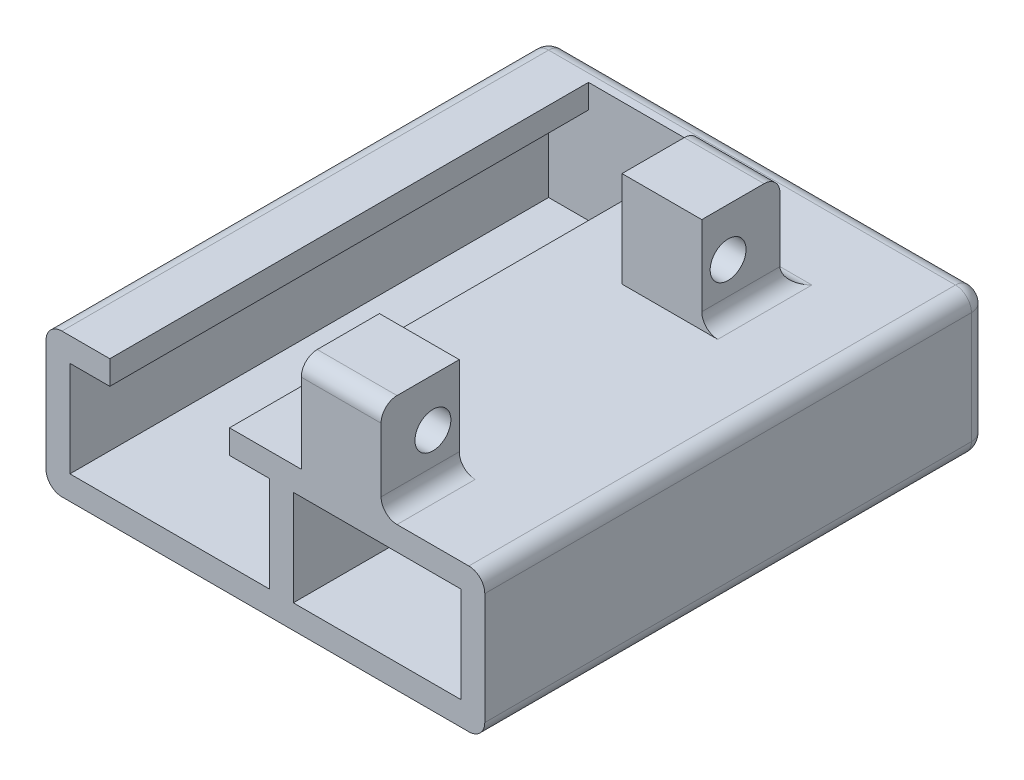
SolidWorks part; units mm, degrees
ref_plane "Front Plane" through (0, 0, 0) normal (0, 0, 1) x (1, 0, 0)
ref_plane "Top Plane" through (0, 0, 0) normal (0, 1, 0) x (1, 0, 0)
ref_plane "Right Plane" through (0, 0, 0) normal (1, 0, 0) x (0, 0, -1)
sketch "Sketch1" plane through (0, 0, 0) normal (0, 0, 1) x (1, 0, 0)
  line L0 (17.5093, 21.5886) -> (-9.4907, 21.5886)
  line L3 (-5.4907, 21.5886) -> (13.5093, 21.5886) construction
  line L4 (-11.4907, 21.5886) -> (-7.4907, 21.5886) construction
  line L5 (-9.4907, 18.5886) -> (-9.4907, 6.5886)
  line L6 (-9.4907, 6.5886) -> (-34.4907, 6.5886)
  line L7 (-34.4907, 6.5886) -> (-34.4907, 18.5886)
  line L8 (-34.4907, 21.5886) -> (-37.4907, 21.5886)
  line L9 (-37.4907, 21.5886) -> (-37.4907, 3.5886)
  line L10 (-37.4907, 3.5886) -> (17.5093, 3.5886)
  line L11 (17.5093, 3.5886) -> (17.5093, 21.5886)
  line L12 (-7.4907, 26.1744) -> (-7.4907, 22.5886) construction
  line L14 (14.5093, 18.5886) -> (-6.4907, 18.5886)
  line L15 (14.5093, 18.5886) -> (14.5093, 6.5886)
  line L16 (14.5093, 6.5886) -> (-6.4907, 6.5886)
  line L17 (-6.4907, 18.5886) -> (-6.4907, 6.5886)
  line L18 (-9.4907, 21.5886) -> (-14.4907, 21.5886)
  line L20 (-9.4907, 18.5886) -> (-14.4907, 18.5886)
  line L21 (-14.4907, 21.5886) -> (-14.4907, 18.5886)
  line L22 (-34.4907, 21.5886) -> (-29.4907, 21.5886)
  line L24 (-34.4907, 18.5886) -> (-29.4907, 18.5886)
  line L25 (-29.4907, 21.5886) -> (-29.4907, 18.5886)
  dimension "D1" = 2
  dimension "D2" = 25
  dimension "D3" = 3
  dimension "D4" = 55
  dimension "D5" = 3
  dimension "D6" = 15
  dimension "D7" = 3
  dimension "D8" = 3
  dimension "D9" = 3
  dimension "D10" = 3
  dimension "D11" = 3
  dimension "D12" = 3
  dimension "D13" = 5
  dimension "D14" = 5
extrude "Boss-Extrude1" add sketch "Sketch1" against normal blind 60
sketch "Sketch2" plane through (-5.4907, 0, 0) normal (1, 0, 0) x (0, 0, -1)
  line L0 (39, 33.5886) -> (44.25, 33.5886) construction
  line L1 (50, 21.5886) -> (40.2, 21.5886)
  line L2 (50, 21.5886) -> (50, 31.5886)
  line L3 (48, 33.5886) -> (40.2, 33.5886)
  line L4 (40.2, 21.5886) -> (40.2, 33.5886)
  line L5 (40, 32.5886) -> (40, 22.5886) construction
  line L6 (60, 21.5886) -> (0, 21.5886) construction
  line L7 (9.8, 21.5886) -> (0, 21.5886)
  line L8 (9.8, 21.5886) -> (9.8, 33.5886)
  line L9 (9.8, 33.5886) -> (2, 33.5886)
  line L10 (0, 21.5886) -> (0, 31.5886)
  line L11 (10, 22.5886) -> (10, 32.5886) construction
  line L12 (5.75, 33.5886) -> (11, 33.5886) construction
  line L13 (0, 3.5886) -> (0, 21.5886) construction
  circle A0 centre (43.5, 27.5886) radius 2.25
  circle A1 centre (6.5, 27.5886) radius 2.25
  arc A2 (50, 31.5886) -> (48, 33.5886) centre (48, 31.5886) ccw
  arc A3 (2, 33.5886) -> (0, 31.5886) centre (2, 31.5886) ccw
  dimension "D2" = 4.5
  dimension "D4" = 4.5
  dimension "D5" = 2
  dimension "D1" = 0.2
  dimension "D3" = 0.2
  dimension "D6" = 9.8
extrude "Boss-Extrude2" add sketch "Sketch2" along normal blind 10
sketch "Sketch3" plane through (0, 0, -60) normal (0, 0, -1) x (-1, 0, 0)
  line L1 (-17.5093, 21.5886) -> (37.4907, 21.5886)
  line L2 (-17.5093, 21.5886) -> (-17.5093, 3.5886)
  line L3 (-17.5093, 3.5886) -> (37.4907, 3.5886)
  line L4 (37.4907, 21.5886) -> (37.4907, 3.5886)
extrude "Boss-Extrude3" add sketch "Sketch3" along normal blind 3
fillet "Fillet1" radius 2 11 edges at (17.5093, 21.5886, -31.5) (17.5093, 3.5886, -31.5) (-37.4907, 3.5886, -31.5) (-37.4907, 21.5886, -31.5) (-9.9907, 21.5886, -63) (-37.4907, 12.5886, -63) (-9.9907, 3.5886, -63) (17.5093, 12.5886, -63) (4.5093, 21.5886, -4.9) (-0.4907, 21.5886, -50) (4.5093, 21.5886, -45.1)
